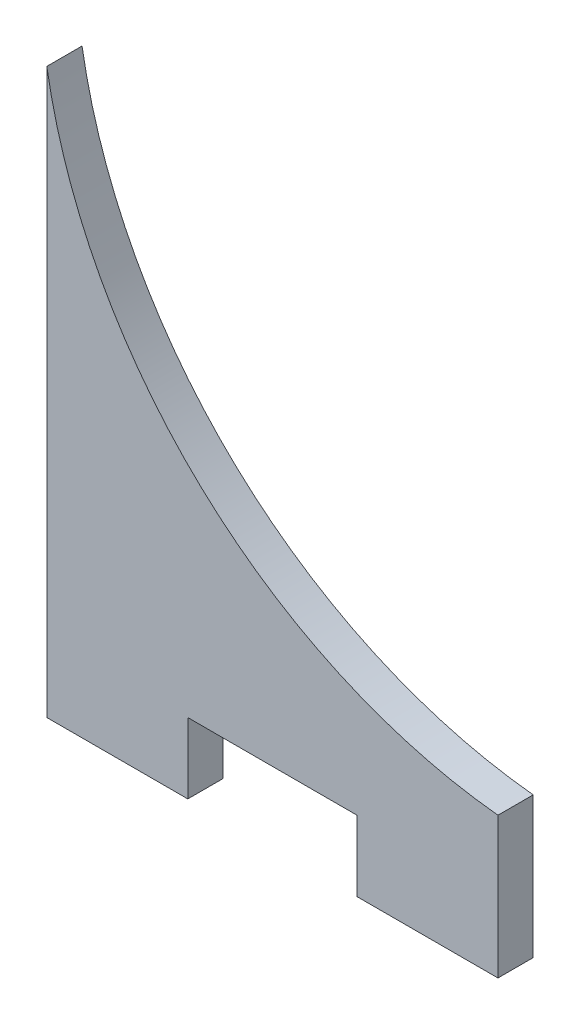
SolidWorks part; units mm, degrees
ref_plane "Front Plane" through (0, 0, 0) normal (0, 0, 1) x (1, 0, 0)
ref_plane "Top Plane" through (0, 0, 0) normal (0, 1, 0) x (1, 0, 0)
ref_plane "Right Plane" through (0, 0, 0) normal (1, 0, 0) x (0, 0, -1)
sketch "Sketch1" plane through (0, 0, 0) normal (0, 0, 1) x (1, 0, 0)
  line L0 (0, 0) -> (81.28, 0)
  line L1 (81.28, 0) -> (81.28, -25.4)
  line L2 (81.28, -25.4) -> (55.88, -25.4)
  line L3 (55.88, -25.4) -> (55.88, -12.7)
  line L4 (55.88, -12.7) -> (25.4, -12.7)
  line L5 (25.4, -12.7) -> (25.4, -25.4)
  line L6 (25.4, -25.4) -> (0, -25.4)
  line L7 (0, -25.4) -> (0, 0)
  line L8 (0, 0) -> (0, 76.2)
  arc A0 (0, 76.2) -> (81.28, 0) centre (90.7979, 91.6017) ccw
  dimension "D7" = 92.0949
  dimension "D1" = 81.28
  dimension "D2" = 25.4
  dimension "D3" = 25.4
  dimension "D4" = 25.4
  dimension "D5" = 25.4
  dimension "D6" = 12.7
  dimension "D8" = 76.2
extrude "Boss-Extrude1" add sketch "Sketch1" along normal blind 6.35 contours A0 L8 L0 | L7 L6 L5 L4 L3 L2 L1 L0
